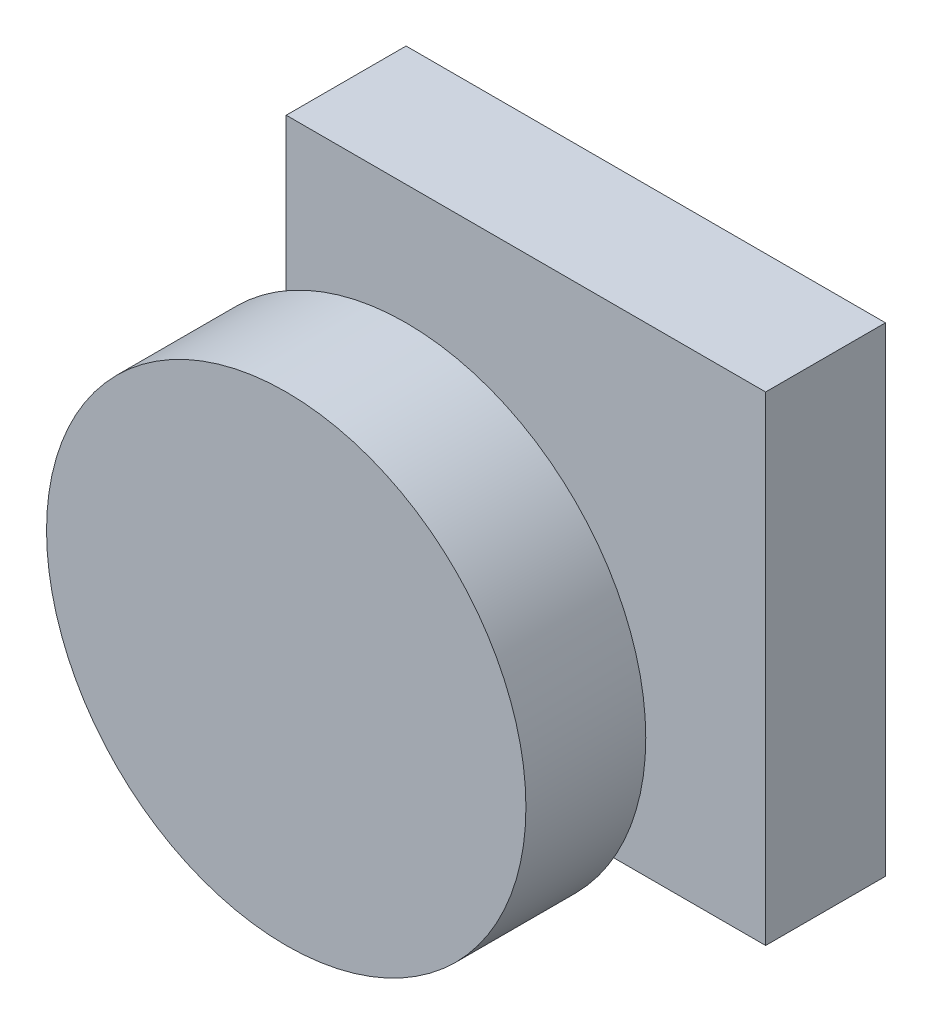
SolidWorks part; units mm, degrees
ref_plane "前基準面" through (0, 0, 0) normal (0, 0, 1) x (1, 0, 0)
ref_plane "上基準面" through (0, 0, 0) normal (0, 1, 0) x (1, 0, 0)
ref_plane "右基準面" through (0, 0, 0) normal (1, 0, 0) x (0, 0, -1)
sketch "草圖1" plane through (0, 0, 0) normal (0, 0, 1) x (1, 0, 0)
  line L1 (-2, 2) -> (2, 2)
  line L2 (-2, 2) -> (-2, -2)
  line L3 (-2, -2) -> (2, -2)
  line L4 (2, 2) -> (2, -2)
  line L5 (-2, 2) -> (2, -2) construction
  line L6 (-2, -2) -> (2, 2) construction
  point P0 (0, 0)
extrude "填料-伸長1" add sketch "草圖1" along normal blind 1 contours L1 L4 L3 L2
sketch "草圖2" plane through (0, 0, 1) normal (0, 0, 1) x (1, 0, 0)
  circle A0 centre (0, 0) radius 0.4
extrude "填料-伸長2" add sketch "草圖2" along normal blind 1 contours A0
sketch "草圖3" plane through (0, 0, 2) normal (0, 0, 1) x (1, 0, 0)
  circle A0 centre (0, 0) radius 2
extrude "填料-伸長3" add sketch "草圖3" along normal blind 1
